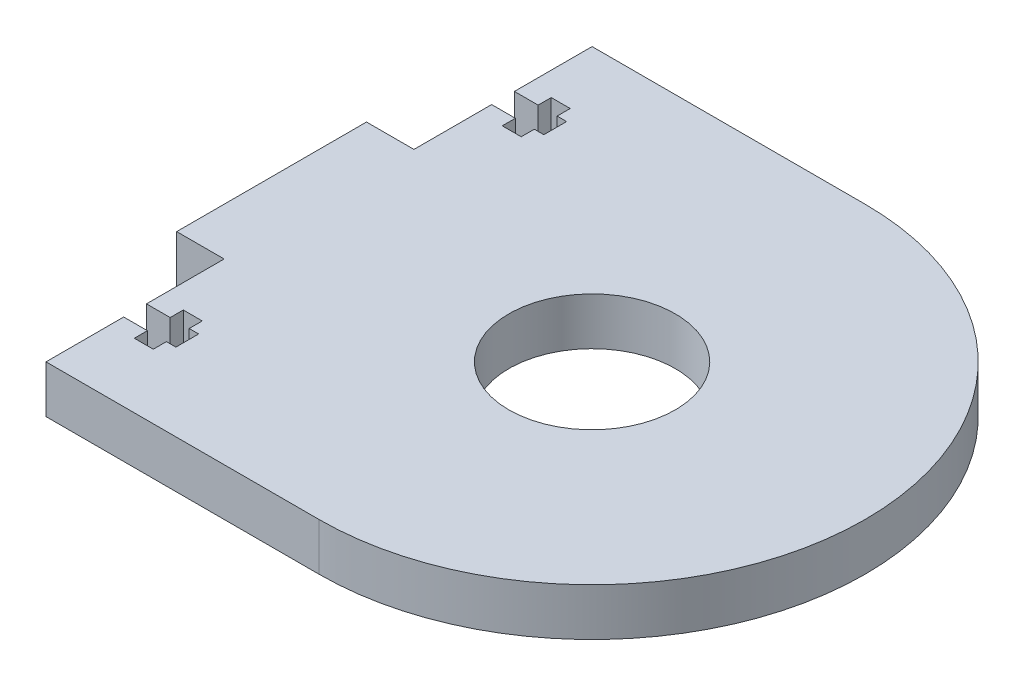
SolidWorks part; units mm, degrees
material "6061 Alloy"
ref_plane "Front Plane" through (0, 0, 0) normal (0, 0, 1) x (1, 0, 0)
ref_plane "Top Plane" through (0, 0, 0) normal (0, 1, 0) x (1, 0, 0)
ref_plane "Right Plane" through (0, 0, 0) normal (1, 0, 0) x (0, 0, -1)
sketch "Sketch1" plane through (0, 0, 0) normal (0, 1, 0) x (1, 0, 0)
  line L0 (-34.1698, 12.2965) -> (-40.5198, 12.2965)
  line L1 (-40.5198, 12.2965) -> (-40.5198, -13.1035)
  line L2 (-40.5198, -13.1035) -> (-34.1698, -13.1035)
  line L3 (2.3681, 36.1344) -> (-34.1698, 36.1344)
  line L4 (-34.1698, 36.1344) -> (-34.1698, 25.7395)
  line L5 (-34.1698, -13.1035) -> (-34.1698, -23.4984)
  line L6 (-34.1698, -36.9414) -> (2.3681, -36.9414)
  line L7 (-27.1848, 25.7395) -> (-28.4548, 25.7395)
  line L8 (-28.4548, 25.7395) -> (-28.4548, 27.4921)
  line L9 (-28.4548, 27.4921) -> (-30.9948, 27.4921)
  line L10 (-30.9948, 27.4921) -> (-30.9948, 25.7395)
  line L11 (-30.9948, 25.7395) -> (-34.1698, 25.7395)
  line L12 (-27.1848, 22.6916) -> (-28.4548, 22.6916)
  line L13 (-28.4548, 22.6916) -> (-28.4548, 20.939)
  line L14 (-28.4548, 20.939) -> (-30.9948, 20.939)
  line L15 (-30.9948, 20.939) -> (-30.9948, 22.6916)
  line L16 (-30.9948, 22.6916) -> (-34.1698, 22.6916)
  line L17 (-27.1848, -23.4984) -> (-28.4548, -23.4984)
  line L18 (-28.4548, -23.4984) -> (-28.4548, -21.7458)
  line L19 (-28.4548, -21.7458) -> (-30.9948, -21.7458)
  line L20 (-30.9948, -21.7458) -> (-30.9948, -23.4984)
  line L21 (-30.9948, -23.4984) -> (-34.1698, -23.4984)
  line L22 (-27.1848, -26.5463) -> (-28.4548, -26.5463)
  line L23 (-28.4548, -26.5463) -> (-28.4548, -28.2989)
  line L24 (-28.4548, -28.2989) -> (-30.9948, -28.2989)
  line L25 (-30.9948, -28.2989) -> (-30.9948, -26.5463)
  line L26 (-30.9948, -26.5463) -> (-34.1698, -26.5463)
  line L27 (-34.1698, 22.6916) -> (-34.1698, 12.2965)
  line L28 (-34.1698, -26.5463) -> (-34.1698, -36.9414)
  line L29 (-27.1848, 25.7395) -> (-27.1848, 22.6916)
  line L30 (-27.1848, -23.4984) -> (-27.1848, -26.5463)
  circle A0 centre (2.3681, -0.4035) radius 11.1379
  arc A1 (2.3681, -36.9414) -> (2.3681, 36.1344) centre (2.3681, -0.4035) ccw
  dimension "D1" = 25.4
  dimension "D2" = 6.35
  dimension "D3" = 36.5379
  dimension "D4" = 6.985
  dimension "D5" = 5.715
  dimension "D6" = 2.54
  dimension "D7" = 1.27
  dimension "D8" = 3.175
  dimension "D9" = 3.0479
  dimension "D10" = 6.5531
extrude "Boss-Extrude1" add sketch "Sketch1" along normal blind 6.35
